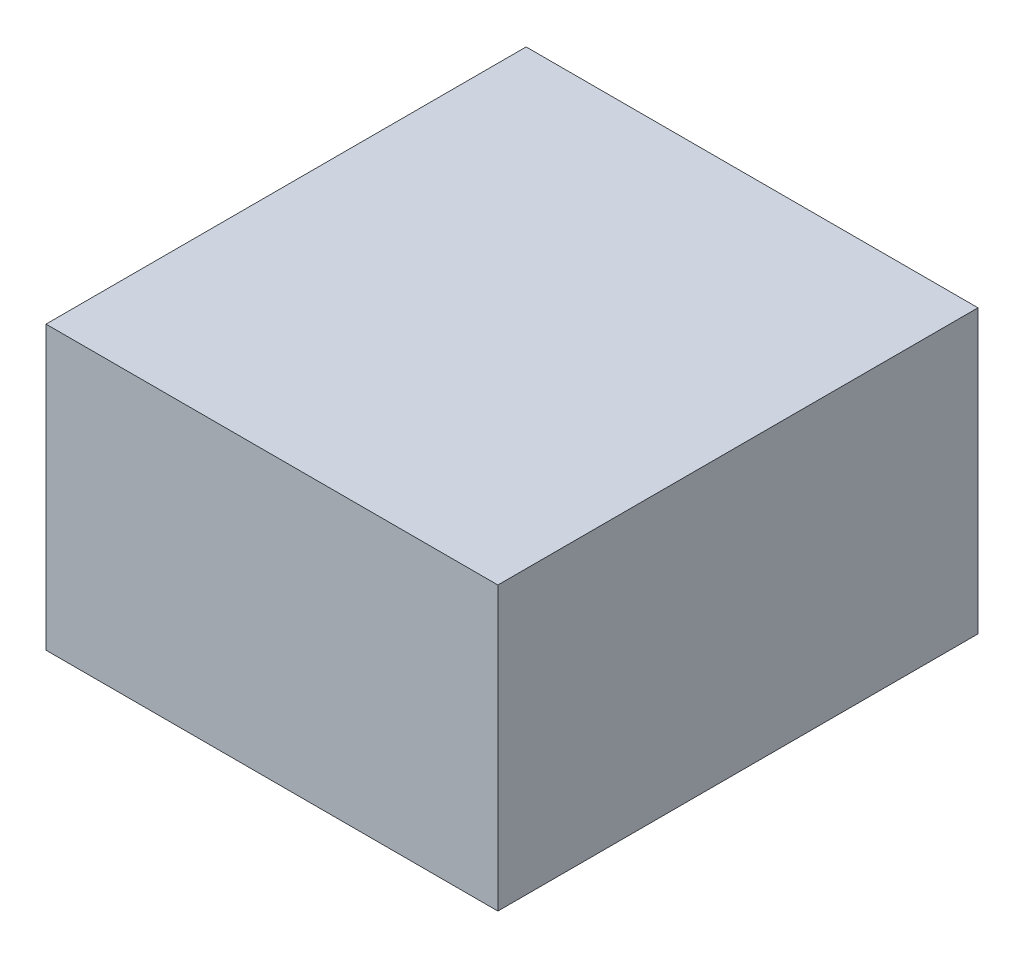
SolidWorks part; units mm, degrees
ref_plane "Front Plane" through (0, 0, 0) normal (0, 0, 1) x (1, 0, 0)
ref_plane "Top Plane" through (0, 0, 0) normal (0, 1, 0) x (1, 0, 0)
ref_plane "Right Plane" through (0, 0, 0) normal (1, 0, 0) x (0, 0, -1)
sketch "Sketch1" plane through (0, 0, 0) normal (0, 1, 0) x (1, 0, 0)
  line L1 (0, 0) -> (-16, 0)
  line L2 (0, 0) -> (0, -17)
  line L3 (0, -17) -> (-16, -17)
  line L4 (-16, 0) -> (-16, -17)
  dimension "D1" = 16
  dimension "D2" = 17
extrude "Boss-Extrude1" add sketch "Sketch1" along normal blind 10
equation "\"largo\"=1.6"
equation "\"D1@Sketch1\"=\"largo\""
equation "\"ancho\"=1.7"
equation "\"D2@Sketch1\"=\"ancho\""
equation "\"alto\"=1"
equation "\"D1@Boss-Extrude1\"=\"alto\""
